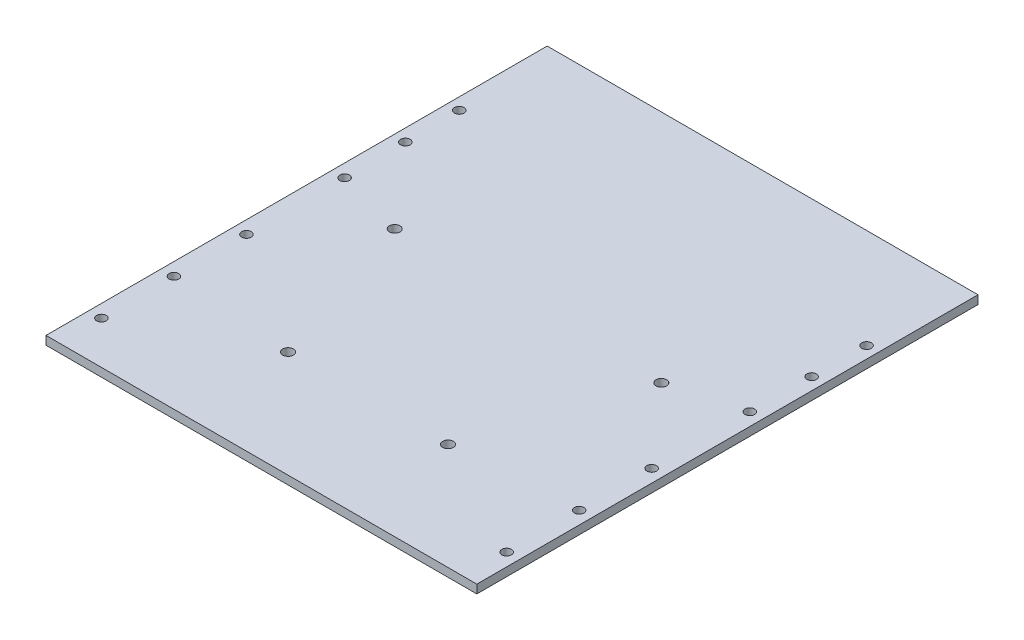
SolidWorks part; units mm, degrees
ref_plane "Front Plane" through (0, 0, 0) normal (0, 0, 1) x (1, 0, 0)
ref_plane "Top Plane" through (0, 0, 0) normal (0, 1, 0) x (1, 0, 0)
ref_plane "Right Plane" through (0, 0, 0) normal (1, 0, 0) x (0, 0, -1)
sketch "Sketch2" plane through (0, 0, 0) normal (0, 1, 0) x (1, 0, 0)
  line L1 (0, 0) -> (404, 0)
  line L2 (0, 0) -> (0, 470)
  line L3 (0, 470) -> (404, 470)
  line L4 (404, 0) -> (404, 470)
  dimension "D1" = 404
  dimension "D2" = 470
extrude "Boss-Extrude1" add sketch "Sketch2" along normal blind 8 contours L2 L1 L4 L3
sketch "Sketch3" plane through (0, 8, 0) normal (0, 1, 0) x (1, 0, 0)
  line L0 (0, 0) -> (404, 0) construction
  line L2 (0, 0) -> (0, 470) construction
  line L3 (404, 0) -> (404, 470) construction
  circle A0 centre (12, 40) radius 4.5
  circle A1 centre (12, 108) radius 4.5
  circle A2 centre (12, 176) radius 4.5
  circle A3 centre (12, 268) radius 4.5
  circle A4 centre (11.5, 325.5) radius 4.5
  circle A5 centre (11, 376.5) radius 4.5
  circle A7 centre (392, 40) radius 4.5
  circle A8 centre (392, 108) radius 4.5
  circle A9 centre (392, 176) radius 4.5
  circle A10 centre (392, 268) radius 4.5
  circle A11 centre (392.5, 325.5) radius 4.5
  circle A12 centre (393, 376.5) radius 4.5
  circle A13 centre (127, 100) radius 5
  circle A14 centre (277, 100) radius 5
  circle A15 centre (77, 250) radius 5
  circle A16 centre (327, 250) radius 5
  point P7 (0, 0)
  dimension "D6" = 11.5
  dimension "D9" = 12
  dimension "D12" = 12
  dimension "D15" = 9
  dimension "D18" = 9
  dimension "D22" = 10
  dimension "D25" = 10
  dimension "D28" = 10
  dimension "D31" = 10
  dimension "D33" = 9
  dimension "D34" = 9
  dimension "D35" = 150
  dimension "D36" = 250
  dimension "D16" = 9
  dimension "D17" = 9
  dimension "D19" = 9
  dimension "D21" = 9
  dimension "D24" = 9
  dimension "D27" = 9
  dimension "D30" = 9
  dimension "D32" = 9
  dimension "D1" = 11
  dimension "D4" = 11.5
  dimension "D5" = 11
  dimension "D7" = 12
  dimension "D8" = 12
  dimension "D10" = 12
  dimension "D11" = 12
  dimension "D13" = 12
  dimension "D14" = 12
  dimension "D20" = 100
  dimension "D23" = 100
  dimension "D26" = 150
  dimension "D29" = 150
extrude "Cut-Extrude1" cut sketch "Sketch3" against normal blind 8
